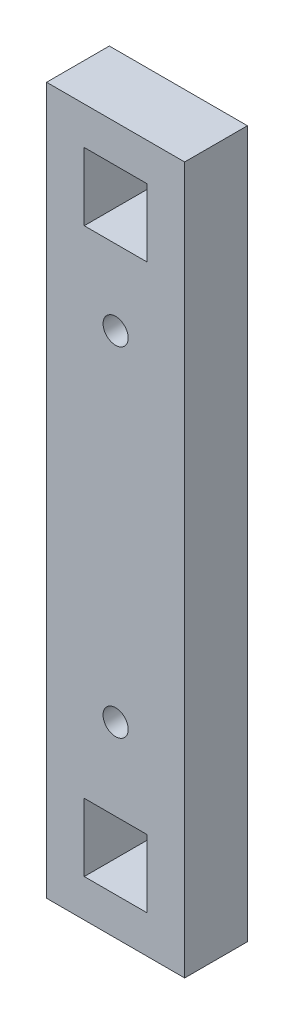
SolidWorks part; units mm, degrees
ref_plane "Plan de face" through (0, 0, 0) normal (0, 0, 1) x (1, 0, 0)
ref_plane "Plan de dessus" through (0, 0, 0) normal (0, 1, 0) x (1, 0, 0)
ref_plane "Plan de droite" through (0, 0, 0) normal (1, 0, 0) x (0, 0, -1)
sketch "Esquisse1" plane through (0, 0, 0) normal (0, 0, 1) x (1, 0, 0)
  line L1 (-6.988, 15.0591) -> (4.012, 15.0591)
  line L2 (-6.988, 15.0591) -> (-6.988, -41.2409)
  line L3 (-6.988, -41.2409) -> (4.012, -41.2409)
  line L4 (4.012, 15.0591) -> (4.012, -41.2409)
  line L5 (-3.988, 12.0591) -> (1.012, 12.0591)
  line L6 (-3.988, 12.0591) -> (-3.988, 6.6591)
  line L7 (-3.988, 6.6591) -> (1.012, 6.6591)
  line L8 (1.012, 12.0591) -> (1.012, 6.6591)
  line L9 (-3.988, -32.8409) -> (1.012, -32.8409)
  line L10 (-3.988, -32.8409) -> (-3.988, -38.2409)
  line L11 (-3.988, -38.2409) -> (1.012, -38.2409)
  line L12 (1.012, -32.8409) -> (1.012, -38.2409)
  circle A2 centre (-1.488, 0.6591) radius 1
  circle A3 centre (-1.488, -26.3409) radius 1
  point P12 (-1.488, -38.2409)
  dimension "D11" = 27
  dimension "D14" = 2
  dimension "D13" = 2
  dimension "D1" = 5
  dimension "D2" = 5.4
  dimension "D3" = 5
  dimension "D4" = 5.4
  dimension "D5" = 3
  dimension "D6" = 3
  dimension "D7" = 3
  dimension "D8" = 3
  dimension "D9" = 3
  dimension "D10" = 39.5
extrude "Boss.-Extru.1" add sketch "Esquisse1" along normal blind 5
move or copy body "Body-Move/Copy1" [suppressed] bodies to move or copy 101
